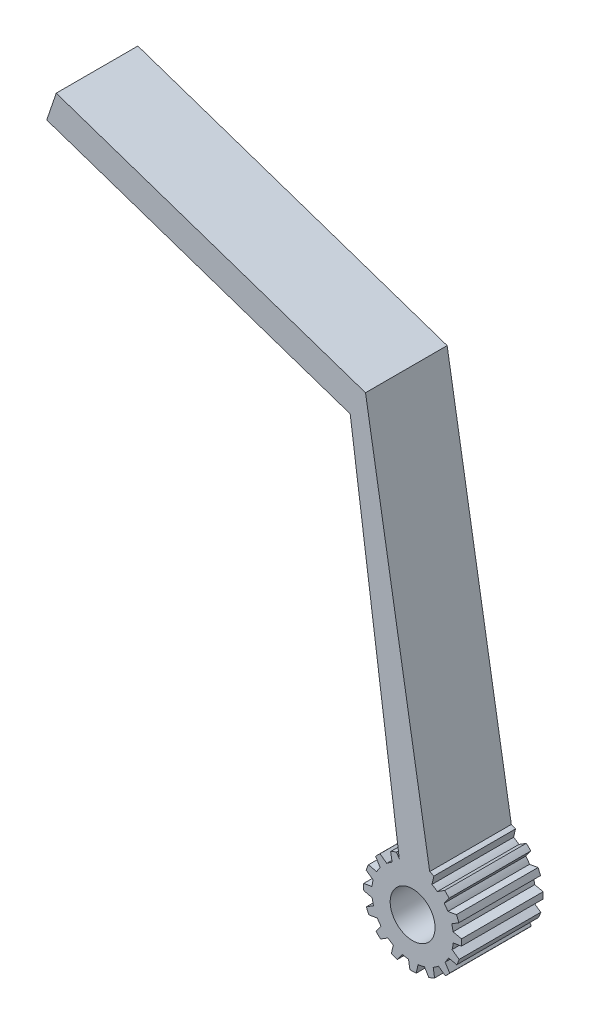
SolidWorks part; units mm, degrees
ref_plane "Front Plane" through (0, 0, 0) normal (0, 0, 1) x (1, 0, 0)
ref_plane "Top Plane" through (0, 0, 0) normal (0, 1, 0) x (1, 0, 0)
ref_plane "Right Plane" through (0, 0, 0) normal (1, 0, 0) x (0, 0, -1)
sketch "Sketch1" plane through (0, 0, 0) normal (0, 0, 1) x (1, 0, 0)
  line L59 (-5.7713, 52.4932) -> (2.0904, 5.6241)
  line L60 (-5.7713, 52.4932) -> (-43.6548, 65.3322)
  line L61 (-43.6548, 65.3322) -> (-44.8161, 61.9056)
  line L62 (-44.8161, 61.9056) -> (-7.6478, 49.3091)
  line L63 (-7.6478, 49.3091) -> (-1.721, 5.7479)
  line L96 (-1.721, 5.7479) -> (-1.6309, 5.0955)
  line L99 (2.6021, 5.4064) -> (2.3674, 4.404)
  line L100 (3.9228, 4.54) -> (3.0305, 3.977)
  line L101 (4.473, 3.9991) -> (3.8725, 3.1628)
  line L102 (5.3616, 2.6932) -> (4.3217, 2.5145)
  line L103 (5.6629, 1.9829) -> (4.7881, 1.4401)
  line L104 (5.9841, 0.4364) -> (4.955, 0.6693)
  line L105 (5.9906, -0.3351) -> (4.9748, -0.5018)
  line L106 (5.6956, -1.8869) -> (4.8339, -1.2779)
  line L107 (5.4064, -2.6021) -> (4.404, -2.3674)
  line L108 (4.54, -3.9228) -> (3.977, -3.0305)
  line L109 (3.9991, -4.473) -> (3.1628, -3.8725)
  line L110 (2.6932, -5.3616) -> (2.5145, -4.3217)
  line L111 (1.9829, -5.6629) -> (1.4401, -4.7881)
  line L112 (0.4364, -5.9841) -> (0.6693, -4.955)
  line L113 (-0.3351, -5.9906) -> (-0.5018, -4.9748)
  line L114 (-1.8869, -5.6956) -> (-1.2779, -4.8339)
  line L115 (-2.6021, -5.4064) -> (-2.3674, -4.404)
  line L116 (-3.9228, -4.54) -> (-3.0305, -3.977)
  line L117 (-4.473, -3.9991) -> (-3.8725, -3.1628)
  line L118 (-5.3616, -2.6932) -> (-4.3217, -2.5145)
  line L119 (-5.6629, -1.9829) -> (-4.7881, -1.4401)
  line L120 (-5.9841, -0.4364) -> (-4.955, -0.6693)
  line L121 (-5.9906, 0.3351) -> (-4.9748, 0.5018)
  line L122 (-5.6956, 1.8869) -> (-4.8339, 1.2779)
  line L123 (-5.4064, 2.6021) -> (-4.404, 2.3674)
  line L124 (-4.54, 3.9228) -> (-3.977, 3.0305)
  line L125 (-3.9991, 4.473) -> (-3.1628, 3.8725)
  line L126 (-2.6932, 5.3616) -> (-2.5145, 4.3217)
  line L127 (-1.9829, 5.6629) -> (-1.6309, 5.0955)
  circle A11 centre (0, 0) radius 2.75
  arc A44 (-1.9829, 5.6629) -> (-2.6932, 5.3616) centre (0, 0) ccw
  arc A45 (-3.977, 3.0305) -> (-4.404, 2.3674) centre (0, 0) ccw
  arc A46 (-3.9991, 4.473) -> (-4.54, 3.9228) centre (0, 0) ccw
  arc A47 (-2.5145, 4.3217) -> (-3.1628, 3.8725) centre (0, 0) ccw
  arc A48 (-5.4064, 2.6021) -> (-5.6956, 1.8869) centre (0, 0) ccw
  arc A49 (2.6021, 5.4064) -> (2.0904, 5.6241) centre (0, 0) ccw
  arc A50 (4.473, 3.9991) -> (3.9228, 4.54) centre (0, 0) ccw
  arc A51 (5.6629, 1.9829) -> (5.3616, 2.6932) centre (0, 0) ccw
  arc A52 (5.9906, -0.3351) -> (5.9841, 0.4364) centre (0, 0) ccw
  arc A53 (5.4064, -2.6021) -> (5.6956, -1.8869) centre (0, 0) ccw
  arc A54 (3.9991, -4.473) -> (4.54, -3.9228) centre (0, 0) ccw
  arc A55 (1.9829, -5.6629) -> (2.6932, -5.3616) centre (0, 0) ccw
  arc A56 (-0.3351, -5.9906) -> (0.4364, -5.9841) centre (0, 0) ccw
  arc A57 (-2.6021, -5.4064) -> (-1.8869, -5.6956) centre (0, 0) ccw
  arc A58 (-4.473, -3.9991) -> (-3.9228, -4.54) centre (0, 0) ccw
  arc A59 (-5.6629, -1.9829) -> (-5.3616, -2.6932) centre (0, 0) ccw
  arc A60 (-5.9906, 0.3351) -> (-5.9841, -0.4364) centre (0, 0) ccw
  arc A61 (3.0305, 3.977) -> (2.3674, 4.404) centre (0, 0) ccw
  arc A62 (4.3217, 2.5145) -> (3.8725, 3.1628) centre (0, 0) ccw
  arc A63 (4.955, 0.6693) -> (4.7881, 1.4401) centre (0, 0) ccw
  arc A64 (4.8339, -1.2779) -> (4.9748, -0.5018) centre (0, 0) ccw
  arc A65 (3.977, -3.0305) -> (4.404, -2.3674) centre (0, 0) ccw
  arc A66 (2.5145, -4.3217) -> (3.1628, -3.8725) centre (0, 0) ccw
  arc A67 (0.6693, -4.955) -> (1.4401, -4.7881) centre (0, 0) ccw
  arc A68 (-1.2779, -4.8339) -> (-0.5018, -4.9748) centre (0, 0) ccw
  arc A69 (-3.0305, -3.977) -> (-2.3674, -4.404) centre (0, 0) ccw
  arc A70 (-4.3217, -2.5145) -> (-3.8725, -3.1628) centre (0, 0) ccw
  arc A71 (-4.955, -0.6693) -> (-4.7881, -1.4401) centre (0, 0) ccw
  arc A72 (-4.8339, 1.2779) -> (-4.9748, 0.5018) centre (0, 0) ccw
  point P10 (-500000, -491064.5295)
  point P12 (-500000, -491064.5295)
  point P13 (-500000, -491066.3162)
  point P14 (-500000, -491061.3866)
  point P67 (0, 0)
  point P69 (-500000, -491078.7369)
  point P70 (-500000, -491078.7369)
  point P71 (-500000, -491078.2203)
  point P86 (0, 0)
  point P139 (0, 0)
other "Pen Sketch1" parameters "D1"=82.4765, "D2"=7.8204, "D5"=10.6989, "D6"=20, "D7"=15, "D3"=9.3609, "D4"=15.6794
extrude "Boss-Extrude1" add sketch "Sketch1" along normal blind 10
